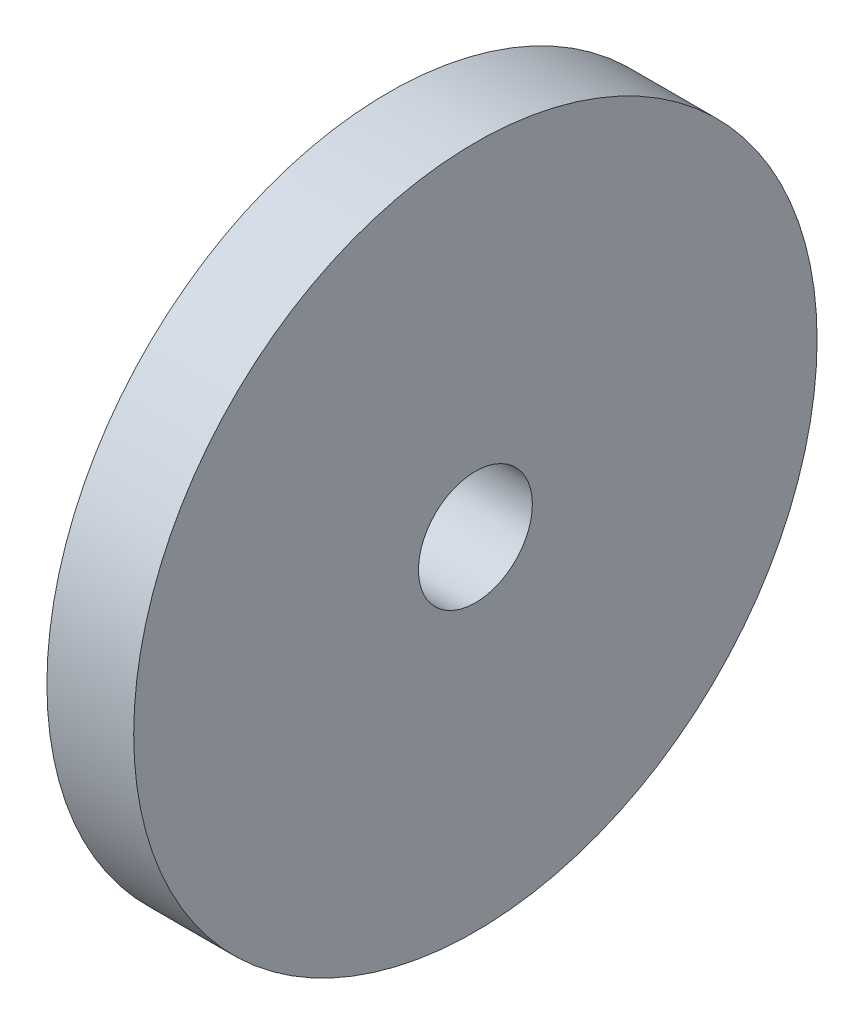
SolidWorks part; units mm, degrees
ref_plane "Plan de face" through (0, 0, 0) normal (0, 0, 1) x (1, 0, 0)
ref_plane "Plan de dessus" through (0, 0, 0) normal (0, 1, 0) x (1, 0, 0)
ref_plane "Plan de droite" through (0, 0, 0) normal (1, 0, 0) x (0, 0, -1)
sketch "Esquisse1" plane through (0, 0, 0) normal (0, 1, 0) x (1, 0, 0)
  line L0 (0, 0) -> (8, 0)
  line L1 (8, 0) -> (8, 31.5)
  line L2 (8, 31.5) -> (0, 31.5)
  line L3 (0, 31.5) -> (0, 0)
  dimension "D1" = 31.5
  dimension "D2" = 8
revolve "Révolution1" add sketch "Esquisse1" angle 360 about L2
sketch "Esquisse2" plane through (8, 0, 0) normal (1, 0, 0) x (0, 0, -1)
  line L0 (0, 0) -> (63, 0) construction
  circle A0 centre (31.5, 0) radius 31.5 construction
  circle A1 centre (31.5, 0) radius 5.25
  dimension "D1" = 10.5
extrude "Enlèv. mat.-Extru.1" cut sketch "Esquisse2" against normal blind 10
